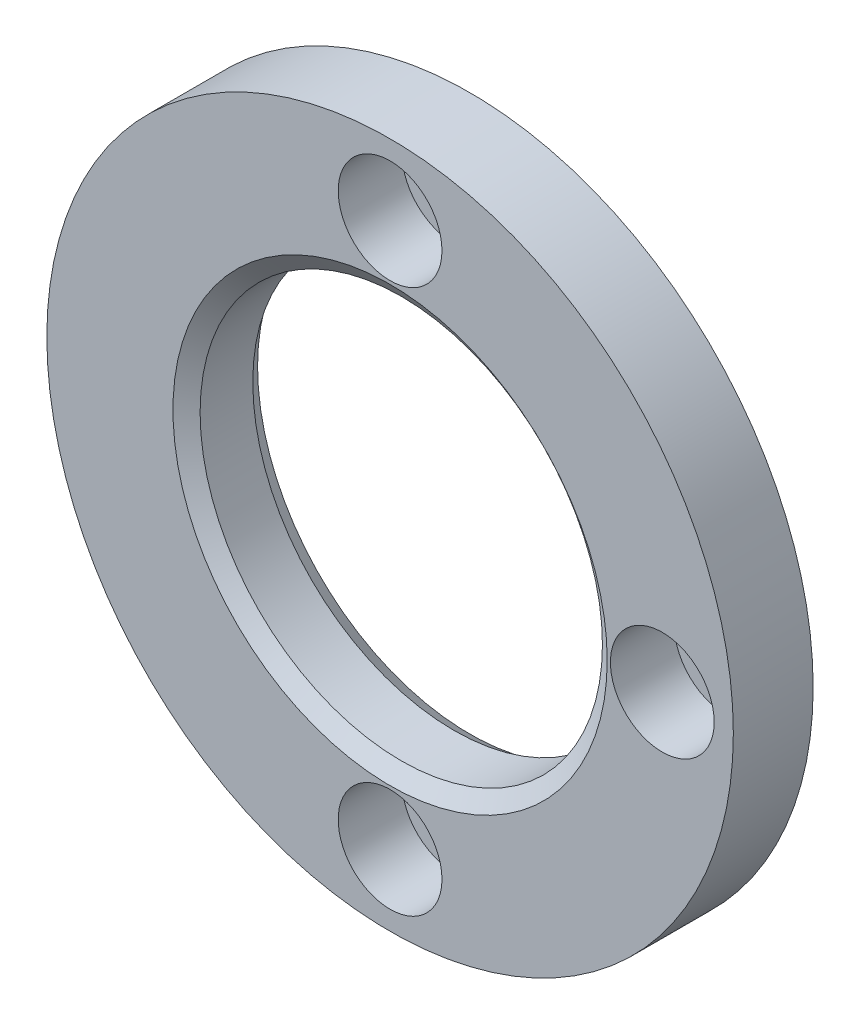
SolidWorks part; units mm, degrees
ref_plane "Front Plane" through (0, 0, 0) normal (0, 0, 1) x (1, 0, 0)
ref_plane "Top Plane" through (0, 0, 0) normal (0, 1, 0) x (1, 0, 0)
ref_plane "Right Plane" through (0, 0, 0) normal (1, 0, 0) x (0, 0, -1)
sketch "Sketch1" plane through (0, 0, 0) normal (0, 0, 1) x (1, 0, 0)
  circle A1 centre (93, 0) radius 43
  circle A2 centre (93, 0) radius 25.2 construction
  circle A3 centre (93, 0) radius 25.2
extrude "Boss-Extrude1" add sketch "Sketch1" along normal blind 10
ref_plane "Plane1" through (0, 0, 2) normal (0, 0, 1) x (1, 0, 0)
sketch "Sketch2" plane through (0, 0, 2) normal (0, 0, 1) x (1, 0, 0)
  circle A1 centre (93, 34.1) radius 6.5
  circle A2 centre (93, 34.1) radius 6.5
  circle A3 centre (127.1, 0) radius 6.5
  circle A4 centre (127.1, 0) radius 6.5
  circle A5 centre (93, -34.1) radius 6.5
  circle A6 centre (93, -34.1) radius 6.5
  dimension "D1" = 0
  dimension "D2" = 0
  dimension "D3" = 0
extrude "Cut-Extrude1" cut sketch "Sketch2" along normal through all
chamfer "Chamfer1" distance 2 angle 35 2 edges at (118.2, 0, 0) (118.2, 0, 10)
